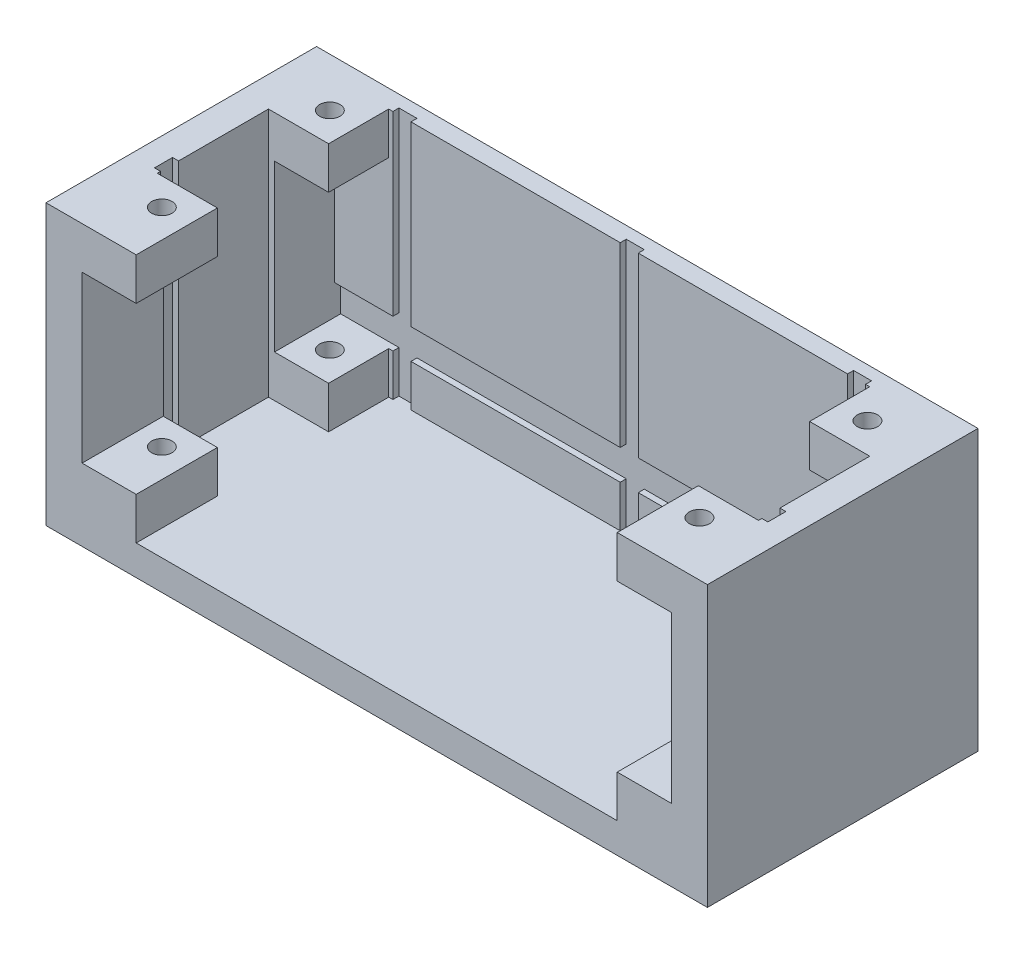
SolidWorks part; units mm, degrees
ref_plane "Front Plane" through (0, 0, 0) normal (0, 0, 1) x (1, 0, 0)
ref_plane "Top Plane" through (0, 0, 0) normal (0, 1, 0) x (1, 0, 0)
ref_plane "Right Plane" through (0, 0, 0) normal (1, 0, 0) x (0, 0, -1)
sketch "Sketch1" plane through (0, 0, 0) normal (0, 1, 0) x (1, 0, 0)
  line L1 (0, 0) -> (110, 0)
  line L2 (0, 0) -> (0, 45)
  line L3 (0, 45) -> (110, 45)
  line L4 (110, 0) -> (110, 45)
  dimension "D1" = 45
  dimension "D2" = 110
extrude "Boss-Extrude1" add sketch "Sketch1" along normal blind 46.5
sketch "Sketch2" plane through (0, 46.5, 0) normal (0, 1, 0) x (1, 0, 0)
  line L0 (0, 0) -> (110, 0) construction
  line L1 (5, 42) -> (105, 42)
  line L2 (5, 42) -> (5, 0)
  line L3 (5, 0) -> (105, 0)
  line L4 (105, 42) -> (105, 0)
  line L5 (110, 45) -> (0, 45) construction
  line L6 (0, 45) -> (0, 0) construction
  line L7 (110, 0) -> (110, 45) construction
  dimension "D1" = 3
  dimension "D2" = 5
  dimension "D3" = 5
extrude "Cut-Extrude1" cut sketch "Sketch2" against normal blind 41.5
sketch "Sketch24" plane through (0, 46.5, 0) normal (0, 1, 0) x (1, 0, 0)
  line L0 (105, 42) -> (5, 42) construction
  line L1 (53.5, 43) -> (56.5, 43)
  line L2 (53.5, 43) -> (53.5, 42)
  line L3 (53.5, 42) -> (56.5, 42)
  line L4 (56.5, 43) -> (56.5, 42)
  line L7 (0, 45) -> (0, 0) construction
  line L8 (110, 0) -> (110, 45) construction
  dimension "D1" = 53.5
  dimension "D2" = 53.5
  dimension "D3" = 1
extrude "Cut-Extrude10" cut sketch "Sketch24" against normal blind 41.5
sketch "Sketch26" plane through (0, 5, 0) normal (0, 1, 0) x (1, 0, 0)
  line L0 (5, 42) -> (5, 0) construction
  line L1 (5, 32) -> (15, 32)
  line L2 (5, 32) -> (5, 42)
  line L3 (5, 42) -> (15, 42)
  line L4 (15, 32) -> (15, 42)
  line L5 (53.5, 42) -> (5, 42) construction
  line L6 (5, 42) -> (5, 0) construction
  line L7 (5, 13.5) -> (15, 13.5)
  line L8 (5, 13.5) -> (5, 0)
  line L9 (5, 0) -> (15, 0)
  line L10 (15, 13.5) -> (15, 0)
  line L11 (5, 0) -> (105, 0) construction
  line L12 (105, 0) -> (105, 42) construction
  line L13 (105, 32) -> (95, 32)
  line L14 (105, 32) -> (105, 42)
  line L15 (105, 42) -> (95, 42)
  line L16 (95, 32) -> (95, 42)
  line L17 (105, 42) -> (56.5, 42) construction
  line L18 (105, 0) -> (105, 42) construction
  line L19 (105, 13.5) -> (95, 13.5)
  line L20 (105, 13.5) -> (105, 0)
  line L21 (105, 0) -> (95, 0)
  line L22 (95, 13.5) -> (95, 0)
  dimension "D1" = 10
  dimension "D2" = 10
  dimension "D3" = 13.5
  dimension "D4" = 10
  dimension "D5" = 10
  dimension "D6" = 10
  dimension "D7" = 13.5
  dimension "D8" = 10
extrude "Boss-Extrude2" add sketch "Sketch26" along normal blind 41.5
hole_wizard "M3 Clearance Hole5" positions "Sketch28" profile "Sketch27" hole size "M3" standard "ANSI Metric" end condition through all
sketch "Sketch28" plane through (0, 46.5, 0) normal (0, 1, 0) x (1, 0, 0)
  line L0 (5, 32) -> (5, 13.5) construction
  line L2 (5, 32) -> (5, 13.5) construction
  line L6 (53.5, 42) -> (15, 42) construction
  line L7 (95, 42) -> (56.5, 42) construction
  line L8 (105, 13.5) -> (105, 32) construction
  point P0 (10.295, 36.91)
  point P2 (99.705, 36.91)
  point P4 (99.705, 8.97)
  point P6 (10.295, 8.97)
  dimension "D1" = 89.41
  dimension "D2" = 5.295
  dimension "D3" = 27.94
  dimension "D4" = 27.94
  dimension "D5" = 89.41
  dimension "D6" = 5.295
  dimension "D7" = 5.09
  dimension "D8" = 5.09
  dimension "D9" = 5.295
  dimension "D10" = 5.295
sketch "Sketch27" plane through (10.295, 46.5, -36.91) normal (1, 0, 0) x (0, 0, 1)
  line L0 (0, 0) -> (0, 46.5)
  line L1 (0, 46.5) -> (1.7, 46.5)
  line L2 (1.7, 46.5) -> (1.7, 0)
  line L5 (1.7, 0) -> (0, 0)
  line L11 (0, -6.35) -> (0, 107.95) construction
  dimension "Thru Hole Dia." = 3.4
  dimension "Thru Hole Depth" = 46.5
sketch "Sketch29" plane through (15, 0, 0) normal (1, 0, 0) x (0, 0, -1)
  line L0 (42, 46.5) -> (42, 5) construction
  line L1 (42, 39.5) -> (32, 39.5)
  line L2 (42, 39.5) -> (42, 12)
  line L3 (42, 12) -> (32, 12)
  line L4 (32, 39.5) -> (32, 12)
  line L5 (32, 46.5) -> (32, 5) construction
  line L6 (32, 46.5) -> (42, 46.5) construction
  line L7 (32, 5) -> (42, 5) construction
  line L8 (13.5, 46.5) -> (13.5, 5) construction
  line L9 (13.5, 39.5) -> (0, 39.5)
  line L10 (13.5, 39.5) -> (13.5, 12)
  line L11 (13.5, 12) -> (0, 12)
  line L12 (0, 39.5) -> (0, 12)
  line L13 (0, 46.5) -> (0, 5) construction
  line L14 (0, 46.5) -> (13.5, 46.5) construction
  line L15 (0, 5) -> (13.5, 5) construction
  dimension "D1" = 7
  dimension "D2" = 7
  dimension "D3" = 7
  dimension "D4" = 7
extrude "Cut-Extrude11" cut sketch "Sketch29" against normal blind 9
sketch "Sketch30" plane through (95, 0, 0) normal (-1, 0, 0) x (0, 0, 1)
  line L0 (-42, 46.5) -> (-42, 5) construction
  line L1 (-42, 39.5) -> (-32, 39.5)
  line L2 (-42, 39.5) -> (-42, 12)
  line L3 (-42, 12) -> (-32, 12)
  line L4 (-32, 39.5) -> (-32, 12)
  line L5 (-32, 46.5) -> (-32, 5) construction
  line L6 (-13.5, 46.5) -> (-13.5, 5) construction
  line L7 (-13.5, 39.5) -> (0, 39.5)
  line L8 (-13.5, 39.5) -> (-13.5, 12)
  line L9 (-13.5, 12) -> (0, 12)
  line L10 (0, 39.5) -> (0, 12)
  line L11 (0, 46.5) -> (0, 5) construction
  line L12 (-42, 46.5) -> (-32, 46.5) construction
  line L13 (-42, 5) -> (-32, 5) construction
  line L14 (-13.5, 46.5) -> (0, 46.5) construction
  line L15 (-13.5, 5) -> (0, 5) construction
  dimension "D1" = 7
  dimension "D2" = 7
  dimension "D3" = 7
  dimension "D4" = 7
extrude "Cut-Extrude12" cut sketch "Sketch30" against normal blind 9
sketch "Sketch32" plane through (0, 46.5, 0) normal (0, 1, 0) x (1, 0, 0)
  line L0 (53.5, 42) -> (15, 42) construction
  line L1 (15.698, 42) -> (18.698, 42)
  line L2 (15.698, 42) -> (15.698, 43)
  line L3 (15.698, 43) -> (18.698, 43)
  line L4 (18.698, 42) -> (18.698, 43)
  line L5 (95, 42) -> (56.5, 42) construction
  line L6 (91.302, 42) -> (94.302, 42)
  line L7 (91.302, 42) -> (91.302, 43)
  line L8 (91.302, 43) -> (94.302, 43)
  line L9 (94.302, 42) -> (94.302, 43)
  line L10 (53.5, 43) -> (53.5, 42) construction
  line L11 (56.5, 42) -> (56.5, 43) construction
  dimension "D1" = 1
  dimension "D2" = 3
  dimension "D3" = 3
  dimension "D4" = 1
  dimension "D5" = 34.802
  dimension "D6" = 34.802
extrude "Cut-Extrude14" cut sketch "Sketch32" against normal blind 41.5
sketch "Sketch33" plane through (0, 46.5, 0) normal (0, 1, 0) x (1, 0, 0)
  line L0 (5, 32) -> (5, 13.5) construction
  line L1 (5, 17.05) -> (4, 17.05)
  line L2 (5, 17.05) -> (5, 14.05)
  line L3 (5, 14.05) -> (4, 14.05)
  line L4 (4, 17.05) -> (4, 14.05)
  line L5 (105, 13.5) -> (105, 32) construction
  line L6 (105, 17.05) -> (106, 17.05)
  line L7 (105, 17.05) -> (105, 14.05)
  line L8 (105, 14.05) -> (106, 14.05)
  line L9 (106, 17.05) -> (106, 14.05)
  dimension "D1" = 3
  dimension "D2" = 1
  dimension "D3" = 5.08
  dimension "D4" = 3
  dimension "D5" = 1
  dimension "D6" = 5.08
extrude "Cut-Extrude15" cut sketch "Sketch33" against normal blind 41.5
sketch "Sketch34" plane through (0, 0, -42) normal (0, 0, 1) x (1, 0, 0)
  line L0 (104, 39.5) -> (104, 12) construction
  line L1 (6, 12) -> (104, 12)
  line L2 (6, 12) -> (6, 17)
  line L3 (6, 17) -> (104, 17)
  line L4 (104, 12) -> (104, 17)
  dimension "D1" = 5
extrude "Cut-Extrude16" cut sketch "Sketch34" against normal blind 1
